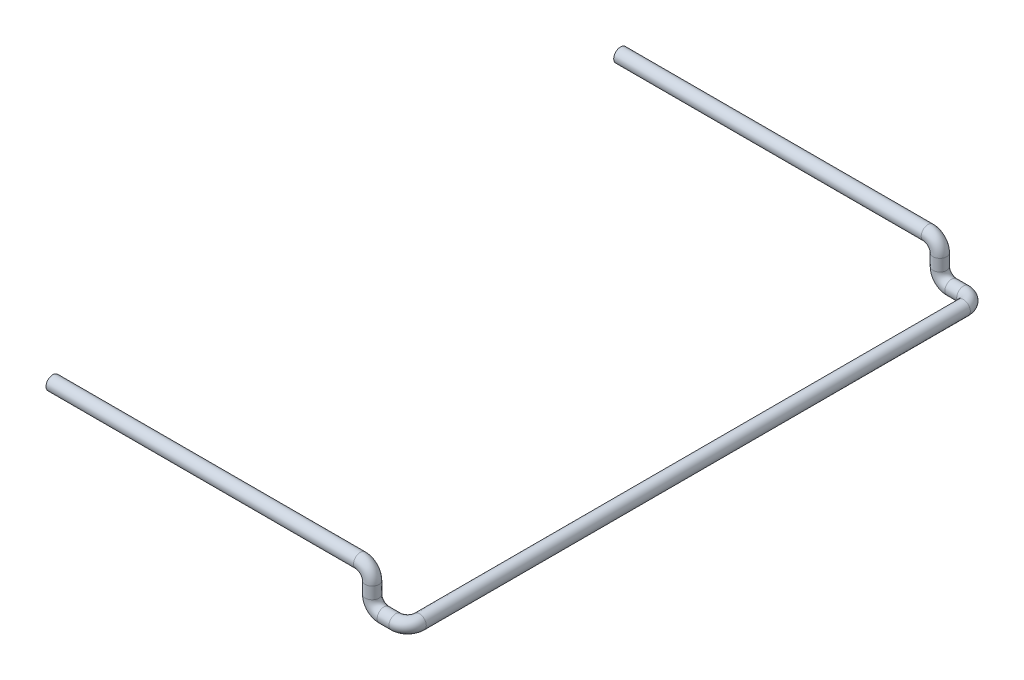
SolidWorks part; units mm, degrees
ref_plane "Front" through (0, 0, 0) normal (0, 0, 1) x (1, 0, 0)
ref_plane "Top" through (0, 0, 0) normal (0, 1, 0) x (1, 0, 0)
ref_plane "Right" through (0, 0, 0) normal (1, 0, 0) x (0, 0, -1)
sketch3d "3DSketch1"
  line L0 (0, 0, 0) -> (130, 0, 0)
  line L1 (135, -5, 0) -> (135, -10, 0)
  line L2 (140, -15, 0) -> (145, -15, 0)
  line L3 (150, -15, 5) -> (150, -15, 235)
  line L4 (145, -15, 240) -> (140, -15, 240)
  line L5 (135, -10, 240) -> (135, -5, 240)
  line L6 (130, 0, 240) -> (0, 0, 240)
  arc A0 (130, 0, 0) -> (135, -5, 0) centre (130, -5, 0) ccw
  arc A1 (135, -10, 0) -> (140, -15, 0) centre (140, -10, 0) ccw
  arc A2 (145, -15, 0) -> (150, -15, 5) centre (145, -15, 5) ccw
  arc A3 (150, -15, 235) -> (145, -15, 240) centre (145, -15, 235) ccw
  arc A4 (140, -15, 240) -> (135, -10, 240) centre (140, -10, 240) ccw
  arc A5 (135, -5, 240) -> (130, 0, 240) centre (130, -5, 240) ccw
  point P11 (135, 0, 0)
  point P12 (130, -5, -5)
  point P15 (135, -15, 0)
  point P16 (140, -10, 5)
  point P19 (150, -15, 0)
  point P20 (145, -20, 5)
  point P23 (150, -15, 240)
  point P24 (145, -20, 235)
  point P27 (135, -15, 240)
  point P28 (140, -10, 235)
  point P31 (135, 0, 240)
  point P32 (130, -5, 245)
  dimension "D8" = 5
  dimension "D1" = 135
  dimension "D2" = 15
  dimension "D3" = 15
  dimension "D4" = 240
  dimension "D5" = 15
  dimension "D6" = 15
  dimension "D7" = 135
sketch "Sketch1" plane through (0, 0, 0) normal (1, 0, 0) x (0, 0, -1)
  circle A0 centre (0, 0) radius 2.8795
  dimension "D1" = 5.759
sweep "Sweep1" add profiles "Sketch1" path "3DSketch1"
sketch "Sketch2" plane through (0, 0, 0) normal (0, 0, 1) x (1, 0, 0)
  line L0 (0, 0) -> (11, 0)
  circle A0 centre (11, 0) radius 2
  dimension "D2" = 4
  dimension "D1" = 11
